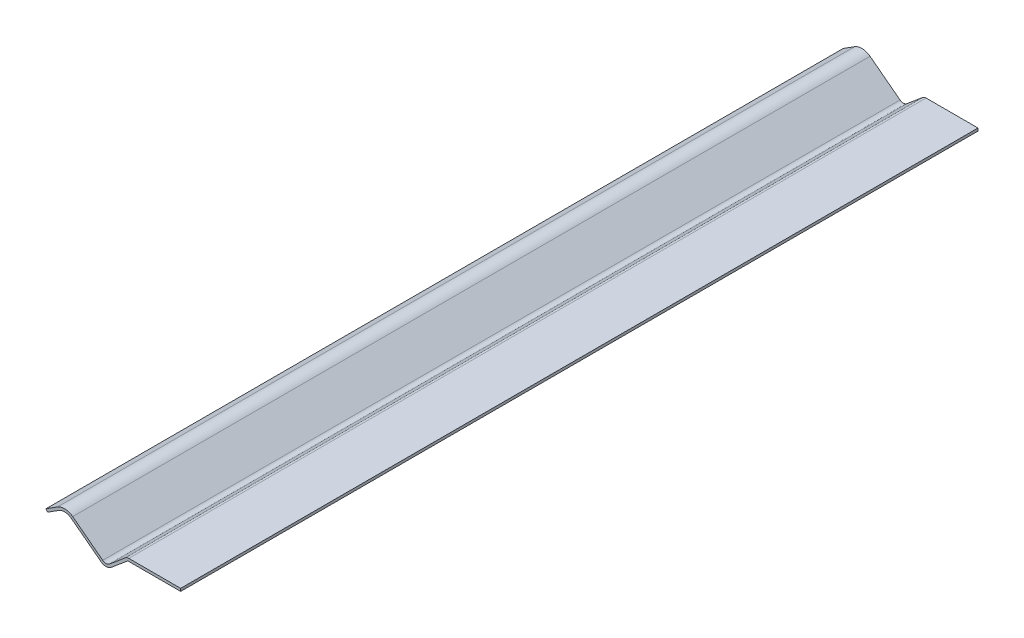
SolidWorks part; units mm, degrees
ref_plane "Front Plane" through (0, 0, 0) normal (0, 0, 1) x (1, 0, 0)
ref_plane "Top Plane" through (0, 0, 0) normal (0, 1, 0) x (1, 0, 0)
ref_plane "Right Plane" through (0, 0, 0) normal (1, 0, 0) x (0, 0, -1)
sketch "Sketch2" plane through (0, 0, 0) normal (0, 0, 1) x (1, 0, 0)
  line L0 (10, 0) -> (0.364, 0)
  line L1 (-0.2788, -0.234) -> (-3.2177, -2.7)
  line L2 (-4.4663, -2.7296) -> (-10.0356, 1.5112)
  line L3 (-12.8883, 1.6338) -> (-15, 0.2956)
  line L4 (10, -0.5) -> (0.364, -0.5)
  line L5 (0.0426, -0.617) -> (-2.8963, -3.083)
  line L6 (-4.7693, -3.1274) -> (-10.3385, 1.1134)
  line L7 (-12.6207, 1.2115) -> (-14.7324, -0.1267)
  line L8 (-15, 0.2956) -> (-14.7324, -0.1267)
  line L9 (10, 0) -> (10, -0.5)
  arc A0 (-10.0356, 1.5112) -> (-12.8883, 1.6338) centre (-11.5501, -0.4778) ccw
  arc A1 (-3.2177, -2.7) -> (-4.4663, -2.7296) centre (-3.8605, -1.934) cw
  arc A2 (0.364, 0) -> (-0.2788, -0.234) centre (0.364, -1) ccw
  arc A3 (0.364, -0.5) -> (0.0426, -0.617) centre (0.364, -1) ccw
  arc A4 (-2.8963, -3.083) -> (-4.7693, -3.1274) centre (-3.8605, -1.934) cw
  arc A5 (-10.3385, 1.1134) -> (-12.6207, 1.2115) centre (-11.5501, -0.4778) ccw
  point P10 (-3.8302, -3.2139)
  point P13 (0, 0)
  dimension "D1" = 10
  dimension "D5" = 2.5
  dimension "D6" = 1
  dimension "D7" = 1
  dimension "D10" = 2.7
  dimension "D2" = 5
  dimension "D3" = 140
  dimension "D4" = 25
  dimension "D8" = 2.5
  dimension "D9" = 7
  dimension "D11" = 0.5
extrude "Boss-Extrude1" add sketch "Sketch2" along normal mid plane 148 contours L3 L8 L7 A5 L6 A4 L5 A3 L4 L9 L0 A2 L1 A1 L2 A0
